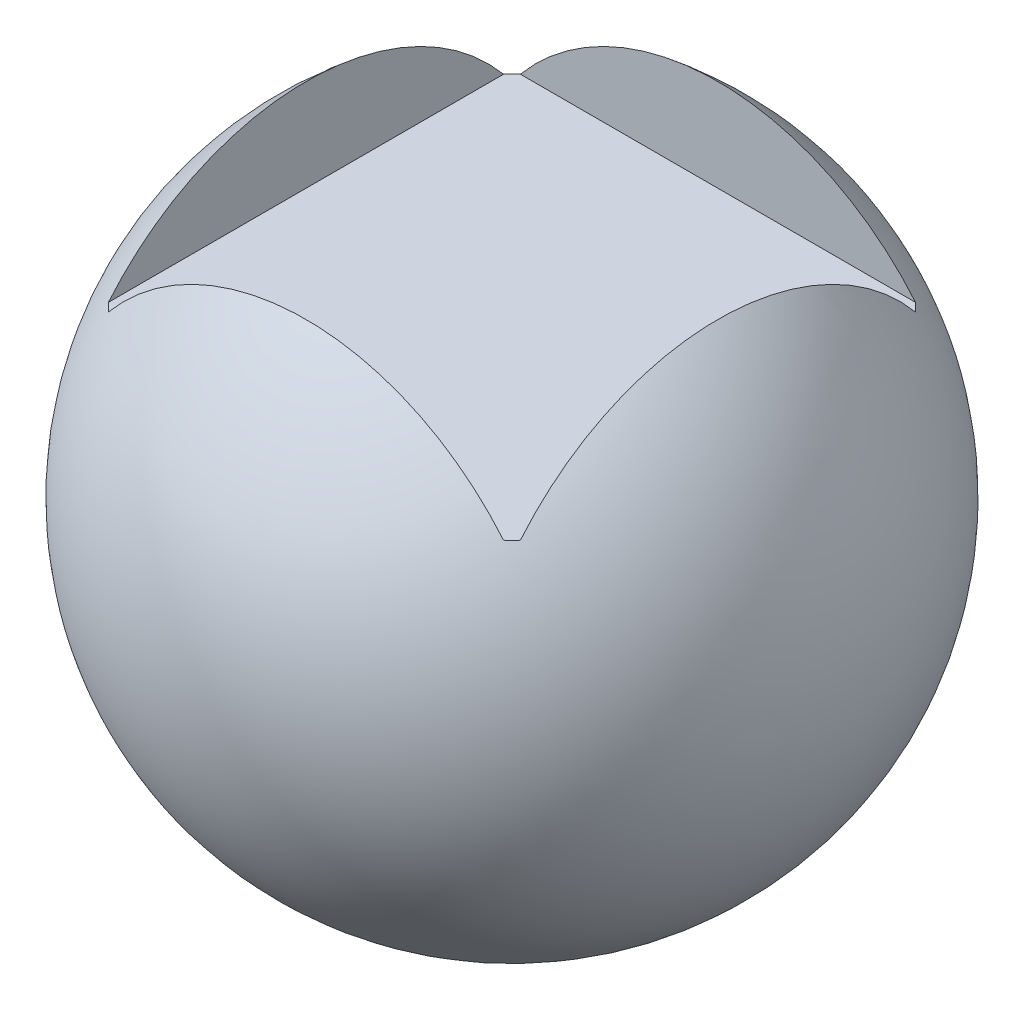
SolidWorks part; units mm, degrees
material "Natural Rubber"
ref_plane "Front Plane" through (0, 0, 0) normal (0, 0, 1) x (1, 0, 0)
ref_plane "Top Plane" through (0, 0, 0) normal (0, 1, 0) x (1, 0, 0)
ref_plane "Right Plane" through (0, 0, 0) normal (1, 0, 0) x (0, 0, -1)
sketch "Sketch1" plane through (0, 0, 0) normal (0, 1, 0) x (1, 0, 0)
  line L0 (0, 88.5978) -> (0, -75.5025) construction
  line L1 (0, 20) -> (0, -20)
  arc A0 (0, 20) -> (0, -20) centre (0, 0) ccw
revolve "Revolve1" add sketch "Sketch1" angle 360 about L0
ref_plane "Plane1" through (0, 10, 0) normal (0, 1, 0) x (1, 0, 0)
sketch "Sketch2" plane through (0, 10, 0) normal (0, 1, 0) x (1, 0, 0)
  line L1 (-12.5, 12.5) -> (12.5, 12.5)
  line L2 (-12.5, 12.5) -> (-12.5, -12.5)
  line L3 (-12.5, -12.5) -> (12.5, -12.5)
  line L4 (12.5, 12.5) -> (12.5, -12.5)
  line L5 (-12.5, 12.5) -> (12.5, -12.5) construction
  line L6 (-12.5, -12.5) -> (12.5, 12.5) construction
  point P0 (0, 0)
  dimension "D1" = 25
  dimension "D2" = 25
extrude "Cut-Extrude1" cut sketch "Sketch2" along normal blind 10
